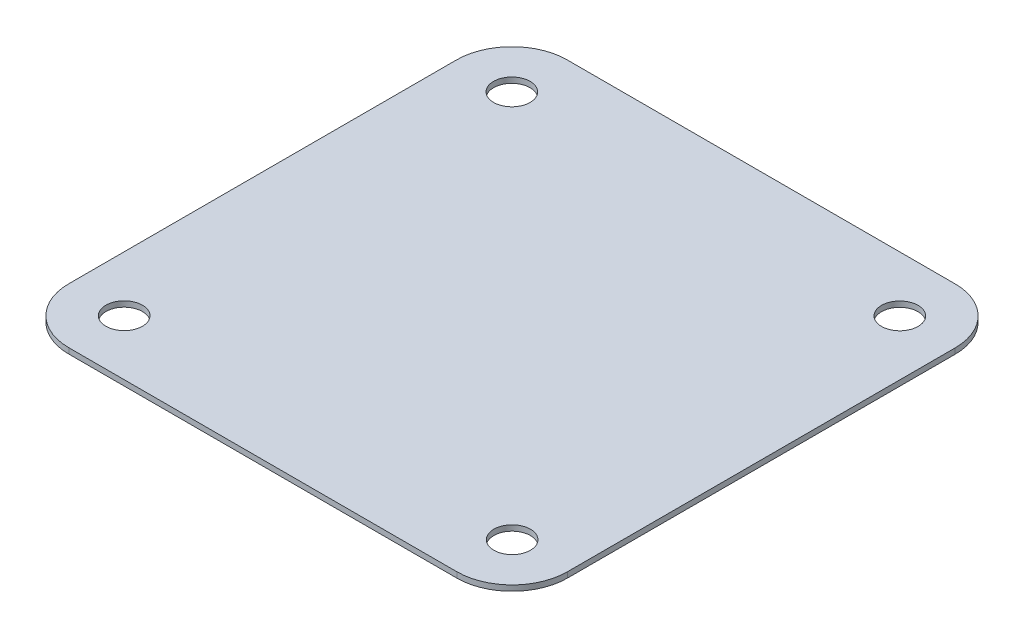
SolidWorks part; units mm, degrees
ref_plane "Front Plane" through (0, 0, 0) normal (0, 0, 1) x (1, 0, 0)
ref_plane "Top Plane" through (0, 0, 0) normal (0, 1, 0) x (1, 0, 0)
ref_plane "Right Plane" through (0, 0, 0) normal (1, 0, 0) x (0, 0, -1)
sketch "Sketch1" plane through (0, 0, 0) normal (0, 1, 0) x (1, 0, 0)
  line L1 (-22.5127, -22.5) -> (22.5127, -22.5)
  line L2 (-22.5127, -22.5) -> (-22.5127, 22.5)
  line L3 (-22.5127, 22.5) -> (22.5127, 22.5)
  line L4 (22.5127, -22.5) -> (22.5127, 22.5)
  line L5 (-22.5127, -22.5) -> (22.5127, 22.5) construction
  line L6 (-22.5127, 22.5) -> (22.5127, -22.5) construction
  circle A0 centre (0, 0) radius 21.05 construction
  circle A1 centre (0, 0) radius 22.5 construction
  point P8 (0, 22.5)
  dimension "D1" = 42.1
  dimension "D2" = 45
extrude "Boss-Extrude1" add sketch "Sketch1" along normal blind 60
sketch "Sketch5" plane through (0, 0, 0) normal (0, -1, 0) x (1, 0, 0)
  line L1 (-22.5127, -22.5) -> (22.5127, -22.5)
  line L2 (-22.5127, -22.5) -> (-22.5127, 22.5)
  line L3 (-22.5127, 22.5) -> (22.5127, 22.5)
  line L4 (22.5127, -22.5) -> (22.5127, 22.5)
  line L5 (-22.5127, -22.5) -> (22.5127, 22.5) construction
  line L6 (-22.5127, 22.5) -> (22.5127, -22.5) construction
  point P0 (0, 0)
fillet "Fillet3" radius 5 1 edges at (22.5127, 30, -22.5)
fillet "Fillet4" radius 5 1 edges at (-22.5127, 30, -22.5)
fillet "Fillet7" radius 5 1 edges at (22.5127, 30, 22.5)
fillet "Fillet8" radius 5 1 edges at (-22.5127, 30, 22.5)
sketch "Sketch9" plane through (0, 60, 0) normal (0, 1, 0) x (1, 0, 0)
  line L0 (-21.0482, -21.0355) -> (21.0482, 21.0355) construction
  arc A0 (-22.5127, -17.5) -> (-17.5127, -22.5) centre (-17.5127, -17.5) ccw construction
  arc A1 (22.5127, 17.5) -> (17.5127, 22.5) centre (17.5127, 17.5) ccw construction
  circle A2 centre (-17.5127, 17.5) radius 1.65
  dimension "D1" = 3.3
extrude "Cut-Extrude6" cut sketch "Sketch9" against normal blind 5
mirror "Mirror2" about plane through (0, 0, 0) normal (1, 0, 0) of "Cut-Extrude6" second plane through (0, 0, 0) second plane normal (0, 0, 1)
sketch "Sketch10" plane through (0, 0, 0) normal (0, -1, 0) x (1, 0, 0)
  line L1 (-27.1814, -23.7565) -> (27.1814, -23.7565)
  line L2 (-27.1814, -23.7565) -> (-27.1814, 23.7565)
  line L3 (-27.1814, 23.7565) -> (27.1814, 23.7565)
  line L4 (27.1814, -23.7565) -> (27.1814, 23.7565)
  line L5 (-27.1814, -23.7565) -> (27.1814, 23.7565) construction
  line L6 (-27.1814, 23.7565) -> (27.1814, -23.7565) construction
  point P0 (0, 0)
extrude "Cut-Extrude7" cut sketch "Sketch10" against normal blind 59.5
